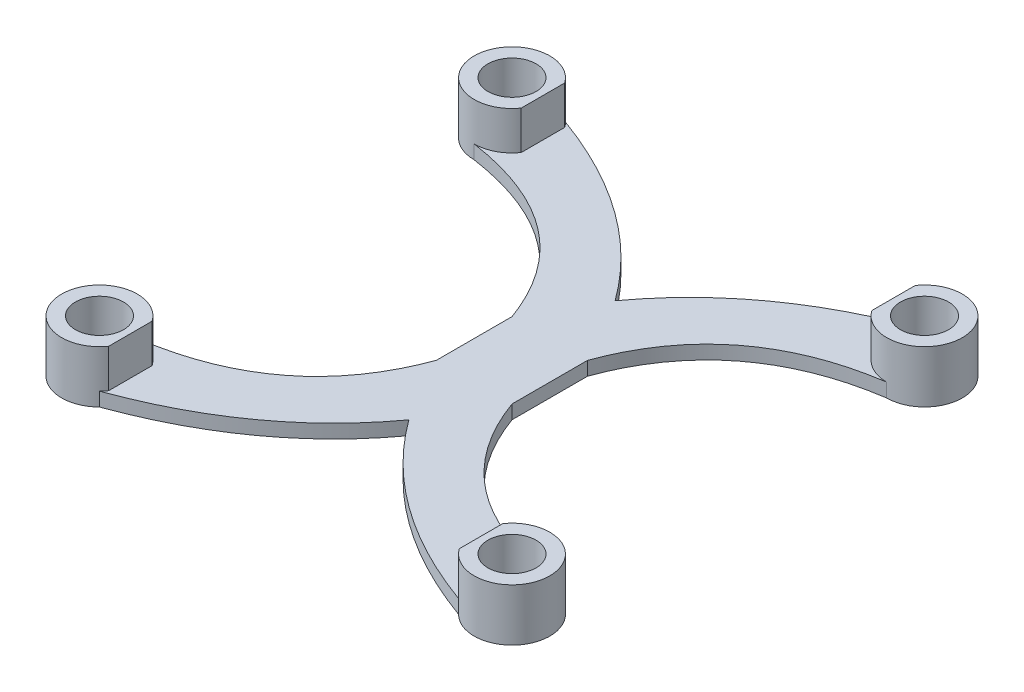
SolidWorks part; units mm, degrees
ref_plane "Front Plane" through (0, 0, 0) normal (0, 0, 1) x (1, 0, 0)
ref_plane "Top Plane" through (0, 0, 0) normal (0, 1, 0) x (1, 0, 0)
ref_plane "Right Plane" through (0, 0, 0) normal (1, 0, 0) x (0, 0, -1)
sketch "Sketch1" plane through (0, 0, 0) normal (0, 1, 0) x (1, 0, 0)
  line L0 (-8.5787, 0) -> (7.286, 0) construction
  line L1 (0, 13.1912) -> (0, -7.1979) construction
  line L2 (-15, 17.75) -> (-12.25, 15) construction
  line L3 (2.75, 2.75) -> (-2.75, 2.75)
  line L4 (2.75, 2.75) -> (2.75, -2.75)
  line L5 (2.75, -2.75) -> (-2.75, -2.75)
  line L6 (-2.75, 2.75) -> (-2.75, -2.75)
  line L7 (2.75, 2.75) -> (-2.75, -2.75) construction
  line L8 (2.75, -2.75) -> (-2.75, 2.75) construction
  line L9 (-13.625, 16.375) -> (-15, 15) construction
  line L10 (-13.625, 16.375) -> (-13.0555, 16.9445) construction
  circle A0 centre (-15, 15) radius 1.75
  circle A1 centre (-15, 15) radius 2.75
  circle A2 centre (15, 15) radius 1.75
  circle A3 centre (15, 15) radius 2.75
  circle A4 centre (15, -15) radius 1.75
  circle A5 centre (15, -15) radius 2.75
  circle A6 centre (-15, -15) radius 2.75
  circle A7 centre (-15, -15) radius 1.75
  spline S0 degree 2 poles (-15, 12.25) (-5.7062, 10.8687) (-2.75, 2.75) knots 0 0 0 1 1 1
  spline S1 degree 2 poles (-13.0555, 16.9445) (-1.8132, 12.864) (2.75, 2.75) knots 0 0 0 1 1 1
  spline S2 degree 2 poles (13.0555, 16.9445) (1.8132, 12.864) (-2.75, 2.75) knots 0 0 0 1 1 1
  spline S3 degree 2 poles (15, 12.25) (5.7062, 10.8687) (2.75, 2.75) knots 0 0 0 1 1 1
  spline S4 degree 2 poles (15, -12.25) (5.7062, -10.8687) (2.75, -2.75) knots 0 0 0 1 1 1
  spline S5 degree 2 poles (13.0555, -16.9445) (1.8132, -12.864) (-2.75, -2.75) knots 0 0 0 1 1 1
  spline S6 degree 2 poles (-13.0555, -16.9445) (-1.8132, -12.864) (2.75, -2.75) knots 0 0 0 1 1 1
  spline S7 degree 2 poles (-15, -12.25) (-5.7062, -10.8687) (-2.75, -2.75) knots 0 0 0 1 1 1
  point P8 (0, 0)
  dimension "D1" = 3.5
  dimension "D4" = 1
  dimension "D2" = 30
  dimension "D3" = 15
  dimension "D5" = 5.5
  dimension "D6" = 5.5
  dimension "D7" = 7.5
  dimension "D8" = 2.75
extrude "Boss-Extrude1" add sketch "Sketch1" along normal blind 1 contours A6 A7 | S7 A6 S6 S5 | S5 S6 L5 | L3 L6 L5 L4 | S6 S5 A5 S4 | A5 A4 | S3 A3 S2 S1 | A3 A2 | S1 S2 L3 | S2 S1 A1 S0 | A1 A0
sketch "Sketch2" plane through (0, 1, 0) normal (0, 1, 0) x (1, 0, 0)
  line L0 (0, 7.5) -> (0, -7.5) construction
  line L1 (-2.75, 0) -> (2.75, 0) construction
  line L2 (-2.75, 2.75) -> (-2.75, -2.75) construction
  line L3 (2.75, 2.75) -> (2.75, -2.75) construction
  circle A0 centre (-15, 15) radius 1.75
  circle A1 centre (-15, 15) radius 1.75 construction
  circle A2 centre (-15, 15) radius 2.75
  arc A3 (-13.0555, 16.9445) -> (-15, 12.25) centre (-15, 15) ccw construction
  circle A4 centre (15, 15) radius 2.75
  circle A5 centre (15, 15) radius 1.75
  circle A6 centre (15, -15) radius 1.75
  circle A7 centre (15, -15) radius 2.75
  circle A8 centre (-15, -15) radius 2.75
  circle A9 centre (-15, -15) radius 1.75
extrude "Boss-Extrude2" add sketch "Sketch2" along normal offset from surface (2.8 mm away) 3.8 up to face at (0, 0, 0)
sketch "Sketch3" plane through (0, 3.8, 0) normal (0, 1, 0) x (1, 0, 0)
  line L1 (12.75, 17.75) -> (-12.75, 17.75)
  line L2 (12.75, 17.75) -> (12.75, -17.75)
  line L3 (12.75, -17.75) -> (-12.75, -17.75)
  line L4 (-12.75, 17.75) -> (-12.75, -17.75)
  line L5 (12.75, 17.75) -> (-12.75, -17.75) construction
  line L6 (12.75, -17.75) -> (-12.75, 17.75) construction
  point P0 (0, 0)
  dimension "D1" = 35.5
  dimension "D2" = 25.5
extrude "Cut-Extrude1" cut sketch "Sketch3" against normal up to surface (2.8 mm away) up to face at (-0.1815, 1, 0.1213)
